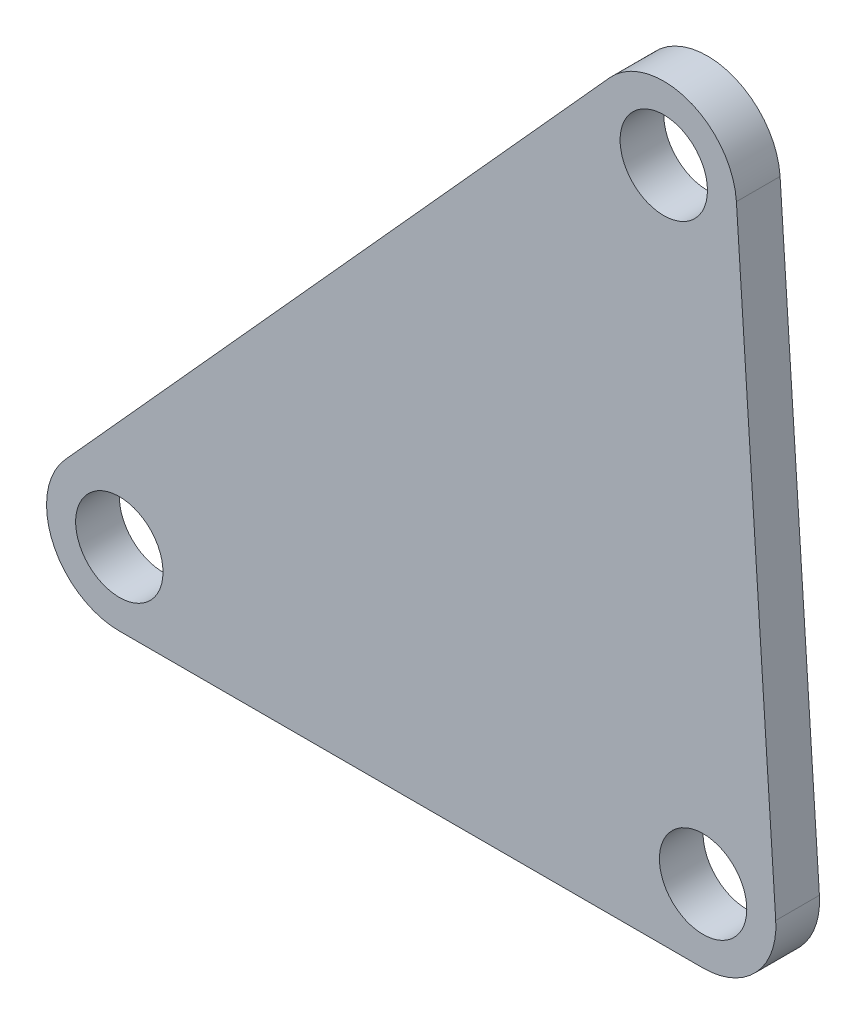
SolidWorks part; units mm, degrees
ref_plane "正面" through (0, 0, 0) normal (0, 0, 1) x (1, 0, 0)
ref_plane "平面" through (0, 0, 0) normal (0, 1, 0) x (1, 0, 0)
ref_plane "右側面" through (0, 0, 0) normal (1, 0, 0) x (0, 0, -1)
sketch "ｽｹｯﾁ1" plane through (0, 0, 0) normal (0, 0, 1) x (1, 0, 0)
  line L0 (0, 0) -> (-40.1, 0) construction
  line L1 (-40.1, 0) -> (-2.701, 41.412) construction
  line L2 (-2.701, 41.412) -> (0, 0) construction
  line L3 (1.5183, 53.5442) -> (-51.3527, -5)
  line L4 (-51.3527, -5) -> (5.3367, -5)
  line L5 (5.3367, -5) -> (1.5183, 53.5442)
  circle A0 centre (-2.701, 41.412) radius 3
  circle A1 centre (-40.1, 0) radius 3
  circle A2 centre (0, 0) radius 3
  dimension "D4" = 6
  dimension "D1" = 40.1
  dimension "D2" = 55.8
  dimension "D3" = 41.5
  dimension "D5" = 5
  dimension "D6" = 5
  dimension "D7" = 5
extrude "ﾎﾞｽ - 押し出し1" add sketch "ｽｹｯﾁ1" along normal blind 3
fillet "ﾌｨﾚｯﾄ1" radius 5 3 edges at (5.3367, -5, 1.5) (1.5183, 53.5442, 1.5) (-51.3527, -5, 1.5)
